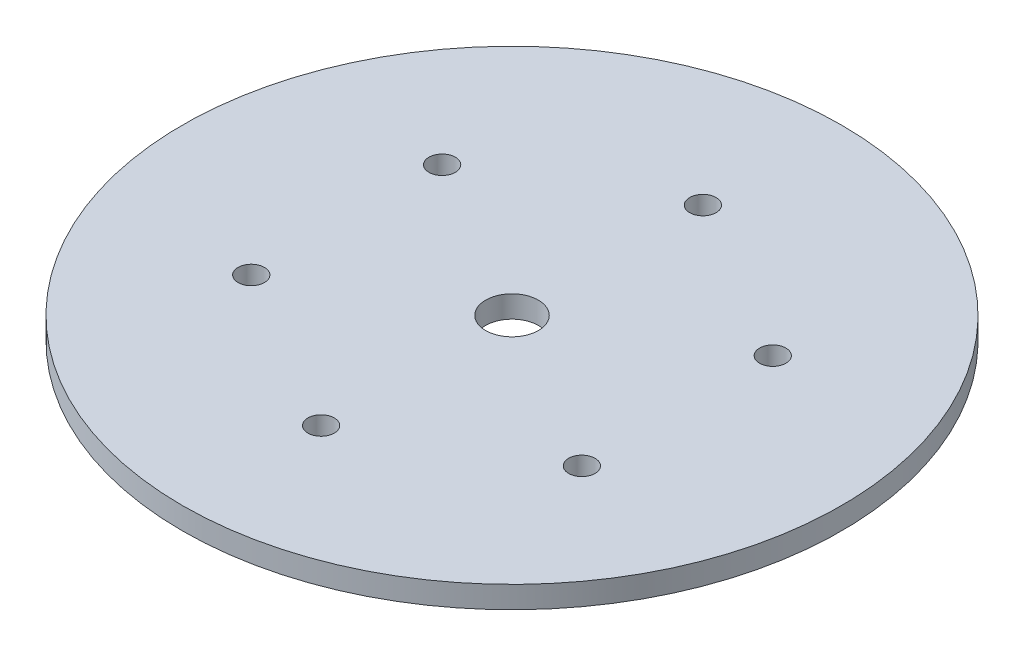
SolidWorks part; units mm, degrees
ref_plane "Front Plane" through (0, 0, 0) normal (0, 0, 1) x (1, 0, 0)
ref_plane "Top Plane" through (0, 0, 0) normal (0, 1, 0) x (1, 0, 0)
ref_plane "Right Plane" through (0, 0, 0) normal (1, 0, 0) x (0, 0, -1)
sketch "Sketch1" plane through (0, 0, 0) normal (0, 1, 0) x (1, 0, 0)
  circle A0 centre (0, 0) radius 75
  circle A1 centre (0, 43.4423) radius 3
  circle A2 centre (37.6222, 21.7212) radius 3
  circle A3 centre (37.6222, -21.7212) radius 3
  circle A4 centre (0, -43.4423) radius 3
  circle A5 centre (-37.6222, -21.7212) radius 3
  circle A6 centre (-37.6222, 21.7212) radius 3
  circle A7 centre (0, 0) radius 6
  point P17 (0, 0)
  dimension "D1" = 150
  dimension "D2" = 6
  dimension "D3" = 6
extrude "Boss-Extrude1" add sketch "Sketch1" along normal blind 5
